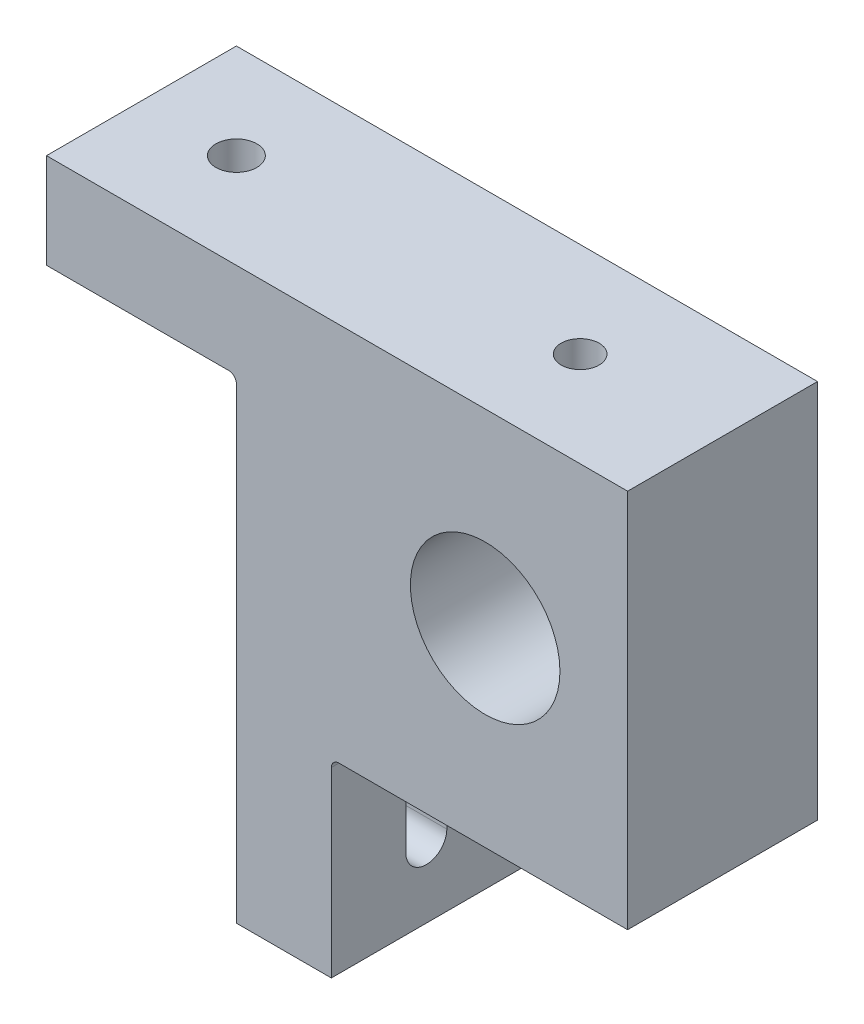
SolidWorks part; units mm, degrees
ref_plane "Front Plane" through (0, 0, 0) normal (0, 0, 1) x (1, 0, 0)
ref_plane "Top Plane" through (0, 0, 0) normal (0, 1, 0) x (1, 0, 0)
ref_plane "Right Plane" through (0, 0, 0) normal (1, 0, 0) x (0, 0, -1)
sketch "Sketch1" plane through (0, 0, 0) normal (0, 0, 1) x (1, 0, 0)
  line L0 (-58.674, 12.7) -> (-33.274, 12.7)
  line L1 (-33.274, 12.7) -> (-33.274, -50.8)
  line L2 (-33.274, -50.8) -> (-20.574, -50.8)
  line L3 (-20.574, -50.8) -> (-20.574, -25.4)
  line L4 (-58.674, 12.7) -> (-58.674, 25.4)
  line L5 (-19.05, -25.4) -> (19.05, -25.4) construction
  line L6 (-19.05, -25.4) -> (-19.05, 25.4) construction
  line L7 (-19.05, 25.4) -> (19.05, 25.4) construction
  line L8 (19.05, -25.4) -> (19.05, 25.4) construction
  line L9 (-19.05, -25.4) -> (19.05, 25.4) construction
  line L10 (-19.05, 25.4) -> (19.05, -25.4) construction
  line L11 (-58.674, 25.4) -> (19.05, 25.4)
  line L12 (19.05, 25.4) -> (19.05, -25.4)
  line L13 (19.05, -25.4) -> (-20.574, -25.4)
  circle A0 centre (0, 0) radius 10
  dimension "D1" = 20
  dimension "D2" = 25.4
  dimension "D3" = 19.05
  dimension "D4" = 12.7
  dimension "D5" = 12.7
  dimension "D6" = 25.4
  dimension "D7" = 25.4
  dimension "D8" = 33.274
extrude "Boss-Extrude1" add sketch "Sketch1" along normal blind 25.4
sketch "Sketch2" plane through (0, 25.4, 0) normal (0, 1, 0) x (1, 0, 0)
  line L1 (-58.674, 0) -> (-33.274, 0) construction
  line L2 (-58.674, 0) -> (-58.674, -25.4) construction
  line L3 (-58.674, -25.4) -> (-33.274, -25.4) construction
  line L4 (-33.274, 0) -> (-33.274, -25.4) construction
  line L5 (-58.674, 0) -> (-33.274, -25.4) construction
  line L6 (-58.674, -25.4) -> (-33.274, 0) construction
  line L7 (0, 0) -> (0, -12.7) construction
  circle A0 centre (-45.974, -12.7) radius 2.7432
  circle A1 centre (0, -12.7) radius 2.54
  point P0 (-45.974, -12.7)
  dimension "D1" = 5.4864
  dimension "D2" = 5.08
extrude "Cut-Extrude1" cut sketch "Sketch2" against normal up to surface (25.4 mm away) up to plane "Top Plane"
sketch "Sketch3" plane through (-20.574, 0, 0) normal (1, 0, 0) x (0, 0, -1)
  line L1 (-25.4, -25.4) -> (0, -25.4) construction
  line L2 (-25.4, -25.4) -> (-25.4, -50.8) construction
  line L3 (-25.4, -50.8) -> (0, -50.8) construction
  line L4 (0, -25.4) -> (0, -50.8) construction
  line L5 (-25.4, -25.4) -> (0, -50.8) construction
  line L6 (-25.4, -50.8) -> (0, -25.4) construction
  line L7 (-12.7, -34.925) -> (-12.7, -41.275) construction
  line L8 (-9.9568, -34.925) -> (-9.9568, -41.275)
  line L9 (-15.4432, -34.925) -> (-15.4432, -41.275)
  arc A0 (-9.9568, -34.925) -> (-15.4432, -34.925) centre (-12.7, -34.925) ccw
  arc A1 (-15.4432, -41.275) -> (-9.9568, -41.275) centre (-12.7, -41.275) ccw
  point P0 (-12.7, -38.1)
  point P5 (-12.7, -38.1)
  dimension "D1" = 5.4864
  dimension "D2" = 6.35
extrude "Cut-Extrude2" cut sketch "Sketch3" against normal up to surface (12.7 mm away) up to face at (-33.274, -19.05, 12.7)
fillet "Fillet1" radius 1.016 2 edges at (-20.574, -25.4, 12.7) (-33.274, 12.7, 12.7)
